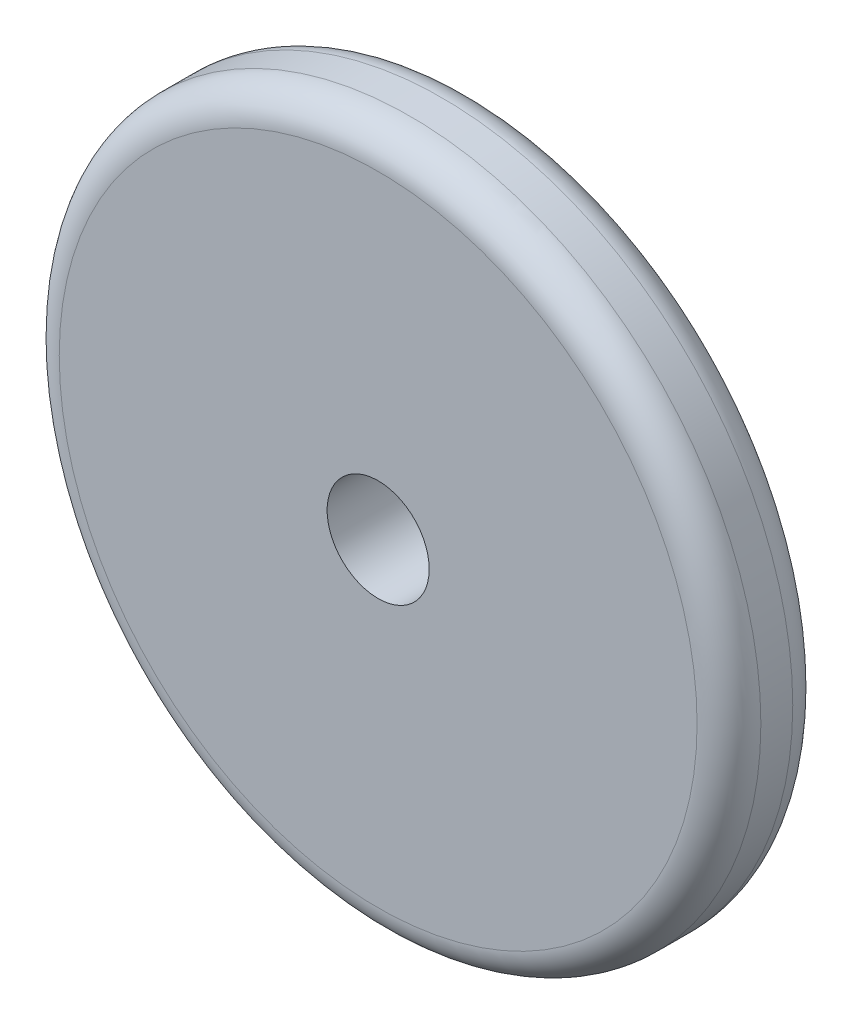
SolidWorks part; units mm, degrees
ref_plane "Front Plane" through (0, 0, 0) normal (0, 0, 1) x (1, 0, 0)
ref_plane "Top Plane" through (0, 0, 0) normal (0, 1, 0) x (1, 0, 0)
ref_plane "Right Plane" through (0, 0, 0) normal (1, 0, 0) x (0, 0, -1)
sketch "Sketch1" plane through (0, 0, 0) normal (0, 0, 1) x (1, 0, 0)
  circle A0 centre (0, 0) radius 11
  circle A1 centre (0, 0) radius 1.6
  dimension "D1" = 22
  dimension "D2" = 3.2
extrude "Boss-Extrude1" add sketch "Sketch1" along normal blind 3
fillet "Fillet1" radius 1 2 edges at (11, 0, 0) (11, 0, 3)
